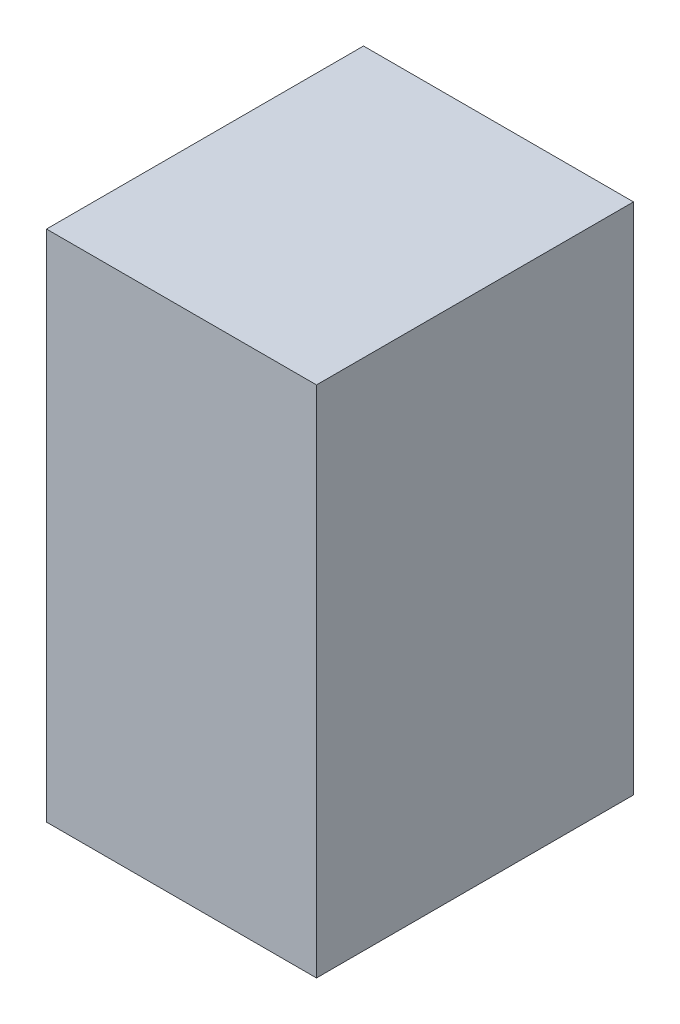
SolidWorks part; units mm, degrees
ref_plane "Front Plane" through (0, 0, 0) normal (1, 0, 0) x (0, 1, 0)
ref_plane "Top Plane" through (0, 0, 0) normal (0, 0, 1) x (0, 1, 0)
ref_plane "Right Plane" through (0, 0, 0) normal (0, 1, 0) x (-1, 0, 0)
sketch "Sketch1" plane through (0, 0, 0) normal (1, 0, 0) x (0, 1, 0)
  line L1 (-33.2918, 20.5473) -> (33.2918, 20.5473)
  line L2 (-33.2918, 20.5473) -> (-33.2918, -20.5473)
  line L3 (-33.2918, -20.5473) -> (33.2918, -20.5473)
  line L4 (33.2918, 20.5473) -> (33.2918, -20.5473)
  line L5 (-33.2918, 20.5473) -> (33.2918, -20.5473) construction
  line L6 (-33.2918, -20.5473) -> (33.2918, 20.5473) construction
  point P0 (0, 0)
extrude "Boss-Extrude1" add sketch "Sketch1" along normal blind 35
